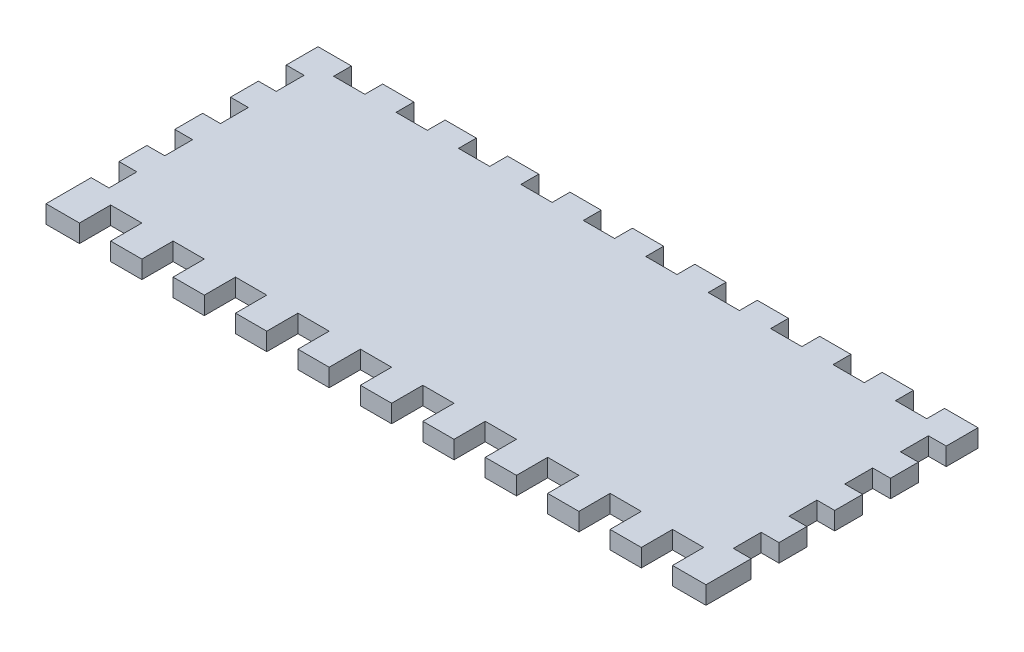
SolidWorks part; units mm, degrees
ref_plane "Piano frontale" through (0, 0, 0) normal (0, 0, 1) x (1, 0, 0)
ref_plane "Piano superiore" through (0, 0, 0) normal (0, 1, 0) x (1, 0, 0)
ref_plane "Piano destro" through (0, 0, 0) normal (1, 0, 0) x (0, 0, -1)
sketch "Schizzo1" plane through (0, 0, 0) normal (0, 1, 0) x (1, 0, 0)
  line L1 (0, 0) -> (140, 0)
  line L2 (0, 0) -> (0, 50)
  line L3 (0, 50) -> (140, 50)
  line L4 (140, 0) -> (140, 50)
  dimension "D1" = 50
  dimension "D2" = 140
extrude "Estrusione-Estrusione1" add sketch "Schizzo1" along normal blind 4
sketch "Schizzo2" plane through (0, 4, 0) normal (0, 1, 0) x (1, 0, 0)
  line L0 (0, 3.125) -> (0, 0)
  line L1 (-4, 3.125) -> (0, 3.125)
  line L2 (-4, 3.125) -> (-4, -7)
  line L3 (-4, -7) -> (3.5, -7)
  line L13 (0, 0) -> (3.5, 0)
  line L18 (3.5, -7) -> (3.5, 0)
  line L19 (0, 0) -> (140, 0) construction
  line L24 (0, 50) -> (0, 0) construction
  line L25 (0, 46.875) -> (-4, 46.875)
  line L26 (-4, 46.875) -> (-4, 54)
  line L27 (-4, 54) -> (3.5, 54)
  line L28 (3.5, 54) -> (3.5, 50)
  line L29 (3.5, 50) -> (0, 50)
  line L30 (0, 50) -> (0, 46.875)
  line L31 (136.5, 50) -> (136.5, 54)
  line L32 (140, 50) -> (0, 50) construction
  line L33 (136.5, 54) -> (144, 54)
  line L34 (144, 54) -> (144, 46.875)
  line L35 (144, 46.875) -> (140, 46.875)
  line L36 (140, 0) -> (140, 50) construction
  line L37 (140, 46.875) -> (140, 50)
  line L38 (140, 50) -> (136.5, 50)
  line L39 (140, 3.125) -> (144, 3.125)
  line L40 (144, 3.125) -> (144, -7)
  line L41 (144, -7) -> (136.5, -7)
  line L42 (136.5, -7) -> (136.5, 0)
  line L43 (136.5, 0) -> (140, 0)
  line L44 (140, 0) -> (140, 3.125)
  dimension "D1" = 7.5
  dimension "D2" = 4
  dimension "D4" = 10.125
  dimension "D5" = 7.125
  dimension "D6" = 7.5
  dimension "D7" = 4
  dimension "D8" = 4
  dimension "D3" = 3.125
extrude "Estrusione-Estrusione2" add sketch "Schizzo2" against normal blind 4
sketch "Schizzo3" plane through (0, 4, 0) normal (0, 1, 0) x (1, 0, 0)
  line L0 (0, 46.875) -> (0, 3.125) construction
  line L1 (0, 40.625) -> (-4, 40.625)
  line L2 (0, 40.625) -> (0, 34.375)
  line L3 (0, 34.375) -> (-4, 34.375)
  line L4 (-4, 40.625) -> (-4, 34.375)
  line L5 (140, 3.125) -> (140, 46.875) construction
  line L6 (140, 40.625) -> (144, 40.625)
  line L7 (140, 40.625) -> (140, 34.375)
  line L8 (140, 34.375) -> (144, 34.375)
  line L9 (144, 40.625) -> (144, 34.375)
  line L10 (-4, 46.875) -> (0, 46.875) construction
  line L11 (144, -7) -> (144, 3.125) construction
  line L12 (-4, 3.125) -> (-4, -7) construction
  dimension "D2" = 6.25
  dimension "D1" = 6.25
extrude "Estrusione-Estrusione3" add sketch "Schizzo3" against normal blind 4
pattern_linear "Ripetizione a L1" count 3 spacing 12.5 along (0, 0, 1) of "Estrusione-Estrusione3"
sketch "Schizzo4" plane through (0, 4, 0) normal (0, 1, 0) x (1, 0, 0)
  line L0 (136.5, 50) -> (3.5, 50) construction
  line L1 (10.5, 50) -> (17.5, 50)
  line L2 (10.5, 50) -> (10.5, 54)
  line L3 (10.5, 54) -> (17.5, 54)
  line L4 (17.5, 50) -> (17.5, 54)
  line L5 (3.5, 0) -> (136.5, 0) construction
  line L6 (10.5, 0) -> (17.5, 0)
  line L7 (10.5, 0) -> (10.5, -7)
  line L8 (10.5, -7) -> (17.5, -7)
  line L9 (17.5, 0) -> (17.5, -7)
  line L11 (-4, -7) -> (3.5, -7) construction
  line L12 (3.5, 54) -> (-4, 54) construction
  line L14 (3.5, 50) -> (3.5, 54) construction
  dimension "D2" = 7
  dimension "D1" = 7
extrude "Estrusione-Estrusione4" add sketch "Schizzo4" against normal blind 4
pattern_linear "Ripetizione a L2" count 9 spacing 14 along (1, 0, 0) of "Estrusione-Estrusione4"
equation "\"WFront\"= 140mm"
equation "\"HFront\"= 80mm"
equation "\"DFront\"= 4mm"
equation "\"WLeft\"= 50mm"
equation "\"HLeft\"= 80mm"
equation "\"DLeft\"= 4mm"
equation "\"WTop\"= 140mm"
equation "\"HTop\"= 50mm"
equation "\"DTop\"= 4mm"
equation "\"N_Denti_W\"= 10"
equation "\"N_Denti_H\"= 7"
equation "\"N_Denti_D\"= 4"
equation "\"HDistDenti\"= \"HFront\" / \"N_Denti_H\""
equation "\"WDistDenti\"= \"WFront\" / \"N_Denti_W\""
equation "\"DDistDenti\"= \"WLeft\" / \"N_Denti_D\""
equation "\"HDenti\"= \"HDistDenti\" / 2"
equation "\"WDenti\"= \"WDistDenti\" / 2"
equation "\"DDenti\"= \"DDistDenti\" / 2"
equation "\"WDisplay\"= 95mm"
equation "\"HDisplay\"= 61mm"
equation "\"CEnc\"= 7mm"
equation "\"Display_to_Enc_W\"= 11.5 + \"CEnc\" / 2"
equation "\"Display_to_Dx\"= 32mm"
equation "\"Display_to_Top\"= 10mm"
equation "\"Display_to_Enc_H\"= 24 + \"CEnc\" / 2"
equation "\"D1@Schizzo1\"=\"HTop\""
equation "\"D2@Schizzo1\"=\"WTop\""
equation "\"D1@Estrusione-Estrusione1\"=\"DTop\""
equation "\"D1@Schizzo2\"=\"DLeft\"+\"WDenti\"/2"
equation "\"D2@Schizzo2\"=\"DLeft\""
equation "\"D4@Schizzo2\"=\"DFront\" + \"DDenti\" / 2 + + \"DMask\""
equation "\"D1@Estrusione-Estrusione2\"=\"DTop\""
equation "\"D3@Ripetizione a L1\"=\"DDistDenti\""
equation "\"D2@Schizzo3\"=\"DDenti\""
equation "\"D1@Estrusione-Estrusione3\"=\"DTop\""
equation "\"D3@Ripetizione a L2\"=\"DDistDenti\""
equation "\"D1@Ripetizione a L2\"=\"N_Denti_W\"-1"
equation "\"D2@Schizzo4\"=\"WDenti\""
equation "\"D1@Estrusione-Estrusione4\"=\"DTop\""
equation "\"D5@Schizzo2\"=\"DDenti\"/2 + \"DFront\""
equation "\"D6@Schizzo2\"=\"DLeft\"+\"WDenti\"/2"
equation "\"D7@Schizzo2\"=\"DLeft\""
equation "\"D8@Schizzo2\"=\"DFront\""
equation "\"D1@Schizzo3\"=\"DDenti\""
equation "\"D1@Ripetizione a L1\"=\"N_Denti_D\"-1"
equation "\"D1@Schizzo4\"=\"WDenti\""
equation "\"D3@Ripetizione a L2\"=\"WDistDenti\""
equation "\"D3@Schizzo2\"=\"DDenti\"/2"
equation "\"DMask\"= 3mm"
